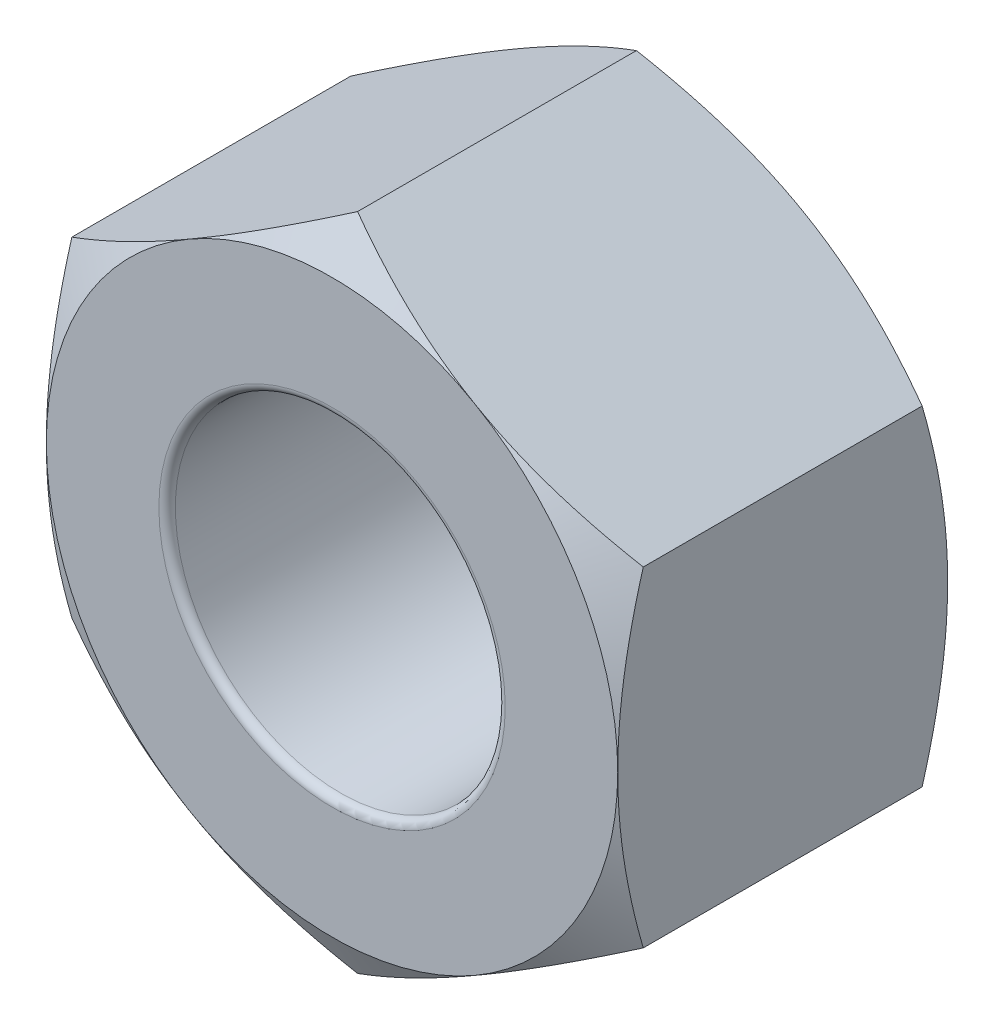
SolidWorks part; units mm, degrees
ref_plane "Front Plane" through (0, 0, 0) normal (0, 0, 1) x (1, 0, 0)
ref_plane "Top Plane" through (0, 0, 0) normal (0, 1, 0) x (1, 0, 0)
ref_plane "Right Plane" through (0, 0, 0) normal (1, 0, 0) x (0, 0, -1)
sketch "Sketch1" plane through (0, 0, 0) normal (0, 0, 1) x (1, 0, 0)
  line L1 (0, 2) -> (-1.7321, 1)
  line L2 (-1.7321, 1) -> (-1.7321, -1)
  line L3 (-1.7321, -1) -> (0, -2)
  line L4 (0, -2) -> (1.7321, -1)
  line L5 (1.7321, -1) -> (1.7321, 1)
  line L6 (1.7321, 1) -> (0, 2)
  circle A0 centre (0, 0) radius 1
  circle A1 centre (0, 0) radius 1.7321 construction
  dimension "D1" = 2
  dimension "D2" = 4
extrude "Boss-Extrude1" add sketch "Sketch1" along normal blind 2
sketch "Sketch7" plane through (0, 0, 2) normal (0, 0, 1) x (1, 0, 0)
  circle A0 centre (0, 0) radius 1.7321 construction
  circle A1 centre (0, 0) radius 1.7321
extrude "Cut-Extrude1" cut sketch "Sketch7" against normal blind 2 draft 60 flip side to cut
sketch "Sketch9" plane through (0, 0, 0) normal (0, 0, -1) x (-1, 0, 0)
  circle A0 centre (0, 0) radius 1.7321 construction
  circle A1 centre (0, 0) radius 1.7321
extrude "Cut-Extrude2" cut sketch "Sketch9" against normal blind 2 draft 60 flip side to cut
fillet "Fillet1" radius 0.05 2 edges at (1, 0, 2) (1, 0, 0)
